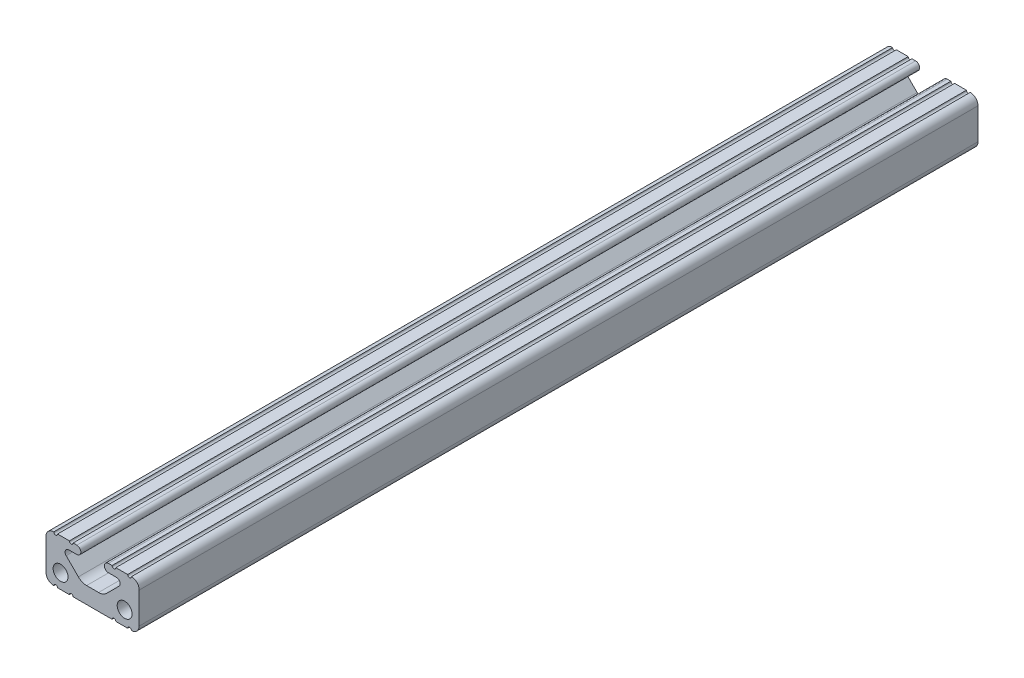
SolidWorks part; units mm, degrees
ref_plane "Front" through (0, 0, 0) normal (0, 0, 1) x (1, 0, 0)
ref_plane "Top" through (0, 0, 0) normal (0, 1, 0) x (1, 0, 0)
ref_plane "Right" through (0, 0, 0) normal (1, 0, 0) x (0, 0, -1)
sketch "Sketch1" plane through (0, 0, 0) normal (0, 0, 1) x (1, 0, 0)
  line L0 (-3.1974, 11.5951) -> (3.1974, 11.5951) construction
  line L1 (-7.504, 9.4742) -> (7.504, 9.4742) construction
  line L28 (-12.7, 10.5918) -> (-12.7, 2.1082)
  line L29 (-9.5504, 0) -> (-6.3246, 0)
  line L30 (-5.3086, 0) -> (5.3086, 0)
  line L31 (6.3246, 0) -> (9.5504, 0)
  line L32 (12.7, 2.1082) -> (12.7, 10.5918)
  line L33 (9.5504, 12.7) -> (6.3246, 12.7)
  line L34 (5.3086, 12.7) -> (4.3023, 12.7)
  line L35 (4.3023, 10.4902) -> (6.488, 10.4902)
  line L36 (7.2064, 8.7558) -> (3.8763, 5.4257)
  line L37 (1.6313, 4.4958) -> (-1.6313, 4.4958)
  line L38 (-3.8763, 5.4257) -> (-7.2064, 8.7558)
  line L39 (-6.488, 10.4902) -> (-4.3023, 10.4902)
  line L40 (-4.3023, 12.7) -> (-5.3086, 12.7)
  line L41 (-6.3246, 12.7) -> (-9.5504, 12.7)
  circle A0 centre (-8.7312, 3.9624) radius 2.032
  circle A1 centre (8.7312, 3.9624) radius 2.032
  arc A36 (-12.7, 2.1082) -> (-10.5791, 0) centre (-10.5918, 2.1082) ccw
  arc A37 (-9.5504, 0) -> (-10.5791, 0) centre (-10.0648, -0.0064) ccw
  arc A38 (-5.3086, 0) -> (-6.3246, 0) centre (-5.8166, 0) ccw
  arc A39 (6.3246, 0) -> (5.3086, 0) centre (5.8166, 0) ccw
  arc A40 (10.5791, 0) -> (9.5504, 0) centre (10.0648, -0.0064) ccw
  arc A41 (10.5791, 0) -> (12.7, 2.1082) centre (10.5918, 2.1082) ccw
  arc A42 (12.7, 10.5918) -> (10.5791, 12.7) centre (10.5918, 10.5918) ccw
  arc A43 (9.5504, 12.7) -> (10.5791, 12.7) centre (10.0648, 12.7063) ccw
  arc A44 (5.3086, 12.7) -> (6.3246, 12.7) centre (5.8166, 12.7) ccw
  arc A45 (4.3023, 12.7) -> (4.3023, 10.4902) centre (4.3023, 11.5951) ccw
  arc A46 (7.2064, 8.7558) -> (6.488, 10.4902) centre (6.488, 9.4742) ccw
  arc A47 (1.6313, 4.4958) -> (3.8763, 5.4257) centre (1.6313, 7.6708) ccw
  arc A48 (-3.8763, 5.4257) -> (-1.6313, 4.4958) centre (-1.6313, 7.6708) ccw
  arc A49 (-6.488, 10.4902) -> (-7.2064, 8.7558) centre (-6.488, 9.4742) ccw
  arc A50 (-4.3023, 10.4902) -> (-4.3023, 12.7) centre (-4.3023, 11.5951) ccw
  arc A51 (-6.3246, 12.7) -> (-5.3086, 12.7) centre (-5.8166, 12.7) ccw
  arc A52 (-10.5791, 12.7) -> (-9.5504, 12.7) centre (-10.0648, 12.7063) ccw
  arc A53 (-10.5791, 12.7) -> (-12.7, 10.5918) centre (-10.5918, 10.5918) ccw
extrude "Boss-Extrude1" add sketch "Sketch1" along normal mid plane 228.6
